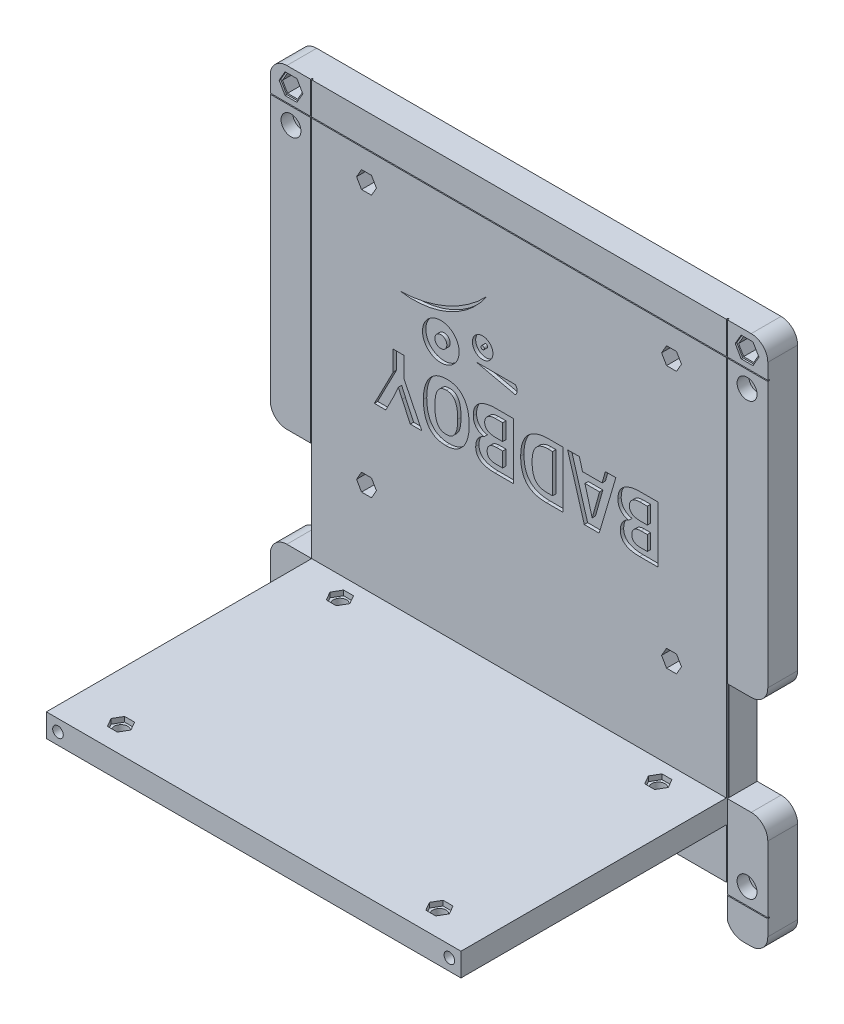
SolidWorks part; units mm, degrees
ref_plane "前基準面" through (0, 0, 0) normal (0, 0, 1) x (1, 0, 0)
ref_plane "上基準面" through (0, 0, 0) normal (0, 1, 0) x (1, 0, 0)
ref_plane "右基準面" through (0, 0, 0) normal (1, 0, 0) x (0, 0, -1)
sketch "草圖1" plane through (0, 0, 0) normal (0, 0, 1) x (1, 0, 0)
  line L0 (-82.0312, 77.5) -> (67.9688, 77.5)
  line L1 (-82.0312, 87.5) -> (67.9688, 87.5)
  line L2 (-82.0312, 87.5) -> (-82.0312, -72.5)
  line L3 (-82.0312, -72.5) -> (67.9688, -72.5)
  line L4 (67.9688, 87.5) -> (67.9688, -72.5)
  line L5 (-82.0312, 87.5) -> (67.9688, -72.5) construction
  line L6 (70, 77.5) -> (67.9688, 87.5)
  line L11 (-69.5312, 87.5) -> (-69.5312, -72.5)
  line L12 (55.4688, 87.5) -> (55.4688, -72.5)
  line L17 (-82.0312, 87.5) -> (-69.5312, 77.5)
  line L19 (-82.0312, 77.5) -> (-69.5312, 87.5)
  line L22 (-79.3612, 82.5) -> (-77.5712, 79.3996)
  line L23 (-77.5712, 79.3996) -> (-73.9912, 79.3996)
  line L24 (-73.9912, 79.3996) -> (-72.2012, 82.5)
  line L25 (-72.2012, 82.5) -> (-73.9912, 85.6004)
  line L26 (-73.9912, 85.6004) -> (-77.5712, 85.6004)
  line L27 (-77.5712, 85.6004) -> (-79.3612, 82.5)
  line L30 (55.4688, 87.5) -> (67.9688, 77.5)
  line L31 (67.9688, -62.5) -> (-82.0312, -62.5)
  line L32 (63.5088, 85.6004) -> (59.9288, 85.6004)
  line L33 (59.9288, 85.6004) -> (58.1388, 82.5)
  line L34 (58.1388, 82.5) -> (59.9288, 79.3996)
  line L35 (59.9288, 79.3996) -> (63.5088, 79.3996)
  line L36 (63.5088, 79.3996) -> (65.2988, 82.5)
  line L37 (65.2988, 82.5) -> (63.5088, 85.6004)
  line L38 (67.9688, -72.5) -> (55.4688, -62.5)
  line L39 (55.4688, -72.5) -> (67.9688, -62.5)
  line L40 (-82.0312, -72.5) -> (-69.5312, -62.5)
  line L41 (-69.5312, -72.5) -> (-82.0312, -62.5)
  line L43 (-77.5712, -64.3996) -> (-79.3612, -67.5)
  line L44 (-79.3612, -67.5) -> (-77.5712, -70.6004)
  line L45 (-77.5712, -70.6004) -> (-73.9912, -70.6004)
  line L46 (-73.9912, -70.6004) -> (-72.2012, -67.5)
  line L47 (-72.2012, -67.5) -> (-73.9912, -64.3996)
  line L48 (-73.9912, -64.3996) -> (-77.5712, -64.3996)
  line L49 (58.1388, -67.5) -> (59.9288, -70.6004)
  line L50 (59.9288, -70.6004) -> (63.5088, -70.6004)
  line L51 (63.5088, -70.6004) -> (65.2988, -67.5)
  line L52 (65.2988, -67.5) -> (63.5088, -64.3996)
  line L53 (63.5088, -64.3996) -> (59.9288, -64.3996)
  line L54 (59.9288, -64.3996) -> (58.1388, -67.5)
  circle A0 centre (-60.98, 68.98) radius 3.1
  circle A1 centre (-60.98, -10.02) radius 3.1
  circle A5 centre (-75.7812, 82.5) radius 3.1004 construction
  circle A6 centre (61.7188, 82.5) radius 3.1004 construction
  circle A7 centre (-75.7812, -67.5) radius 3.1004 construction
  circle A8 centre (61.7188, -67.5) radius 3.1004 construction
  point P0 (0, 0)
  dimension "D8" = 8.52
  dimension "D10" = 79
  dimension "D11" = 5
  dimension "D13" = 3.58
  dimension "D1" = 160
  dimension "D2" = 150
  dimension "D3" = 6.25
  dimension "D4" = 6.25
  dimension "D5" = 12.5
  dimension "D6" = 12.5
  dimension "D7" = 10
  dimension "D9" = 5
  dimension "D12" = 5
  dimension "D14" = 3.58
  dimension "D15" = 10
  dimension "D16" = 3.58
  dimension "D17" = 3.58
  dimension "D18" = 5
  dimension "D19" = 6.25
  dimension "D20" = 6.25
extrude "填料-伸長5" add sketch "草圖1" along normal blind 9 contours L2 L1 L4 L3
sketch "草圖10" plane through (0, 0, 9) normal (0, 0, 1) x (1, 0, 0)
  line L0 (-82.0312, -62.5) -> (67.9688, -62.5)
  line L1 (-82.0312, 87.5) -> (-82.0312, -72.5) construction
  line L2 (67.9688, 87.5) -> (67.9688, -72.5) construction
  line L3 (-82.0312, -72.5) -> (67.9688, -72.5) construction
  line L4 (-69.5312, 87.5) -> (-69.5312, -72.5)
  line L5 (-82.0312, 87.5) -> (67.9688, 87.5) construction
  line L6 (-82.0312, -62.5) -> (-69.5312, -72.5)
  line L8 (-72.2012, -67.5) -> (-73.9912, -64.3996)
  line L9 (-73.9912, -64.3996) -> (-77.5712, -64.3996)
  line L10 (-77.5712, -64.3996) -> (-79.3612, -67.5)
  line L11 (-79.3612, -67.5) -> (-77.5712, -70.6004)
  line L12 (-77.5712, -70.6004) -> (-73.9912, -70.6004)
  line L13 (-73.9912, -70.6004) -> (-72.2012, -67.5)
  circle A0 centre (-75.7812, -67.5) radius 3.1004 construction
  dimension "D1" = 10
  dimension "D2" = 12.5
  dimension "D3" = 3.58
sketch "草圖11" plane through (0, 0, 9) normal (0, 0, 1) x (1, 0, 0)
  line L0 (55.4688, 87.5) -> (55.4688, -72.5)
  line L1 (-82.0312, 87.5) -> (67.9688, 87.5) construction
  line L2 (-82.0312, -72.5) -> (67.9688, -72.5) construction
  line L3 (67.9688, -62.5) -> (-82.0312, -62.5)
  line L4 (67.9688, 87.5) -> (67.9688, -72.5) construction
  line L5 (-82.0312, 87.5) -> (-82.0312, -72.5) construction
  line L6 (67.9688, -62.5) -> (55.4688, -72.5)
  line L8 (65.2988, -67.5) -> (63.5088, -64.3996)
  line L9 (63.5088, -64.3996) -> (59.9288, -64.3996)
  line L10 (59.9288, -64.3996) -> (58.1388, -67.5)
  line L11 (58.1388, -67.5) -> (59.9288, -70.6004)
  line L12 (59.9288, -70.6004) -> (63.5088, -70.6004)
  line L13 (63.5088, -70.6004) -> (65.2988, -67.5)
  circle A0 centre (61.7188, -67.5) radius 3.1004 construction
  dimension "D1" = 10
  dimension "D2" = 12.5
  dimension "D3" = 3.58
sketch "草圖12" plane through (0, 0, 9) normal (0, 0, 1) x (1, 0, 0)
  line L0 (-82.0312, 87.5) -> (67.9688, 87.5) construction
  line L1 (-69.5312, 87.5) -> (-69.5312, -72.5)
  line L2 (-82.0312, -72.5) -> (67.9688, -72.5) construction
  line L3 (-69.5312, -72.5) -> (-69.8312, -72.5)
  line L4 (-69.8312, -72.5) -> (-69.8312, 87.5)
  line L5 (-69.8312, 87.5) -> (-69.5312, 87.5)
  line L6 (-82.0312, 87.5) -> (-82.0312, -72.5) construction
  dimension "D1" = 0.3
  dimension "D2" = 12.5
extrude "除料-伸長8" cut sketch "草圖12" against normal blind 0.5 contours L5 L1 L3 L4
sketch "草圖13" plane through (0, 0, 9) normal (0, 0, 1) x (1, 0, 0)
  line L0 (55.4688, 87.5) -> (55.4688, -72.5)
  line L1 (-69.5312, 87.5) -> (67.9688, 87.5) construction
  line L2 (-69.5312, -72.5) -> (67.9688, -72.5) construction
  line L3 (55.4688, -72.5) -> (55.7675, -72.5)
  line L4 (55.7675, -72.5) -> (55.7675, 87.5)
  line L5 (55.7675, 87.5) -> (55.4688, 87.5)
  line L6 (67.9688, 87.5) -> (67.9688, -72.5) construction
  dimension "D1" = 0.2988
  dimension "D2" = 12.5
extrude "除料-伸長9" cut sketch "草圖13" against normal blind 0.5 contours L5 L0 L3 L4
sketch "草圖19" plane through (0, 0, 9) normal (0, 0, 1) x (1, 0, 0)
  line L0 (-82.0312, 77.5) -> (-69.5312, 77.5)
  line L1 (-82.0312, 87.5) -> (-82.0312, -72.5) construction
  line L2 (-69.5312, 87.5) -> (-69.5312, -72.5) construction
  line L3 (-82.0312, 87.5) -> (-69.8312, 87.5) construction
  line L4 (-82.0312, 87.5) -> (-69.5312, 77.5)
  line L5 (-69.5312, 87.5) -> (-82.0312, 77.5)
  line L7 (-72.2012, 82.5) -> (-73.9912, 85.6004)
  line L8 (-73.9912, 85.6004) -> (-77.5712, 85.6004)
  line L9 (-77.5712, 85.6004) -> (-79.3612, 82.5)
  line L10 (-79.3612, 82.5) -> (-77.5712, 79.3996)
  line L11 (-77.5712, 79.3996) -> (-73.9912, 79.3996)
  line L12 (-73.9912, 79.3996) -> (-72.2012, 82.5)
  circle A0 centre (-75.7812, 82.5) radius 3.1004 construction
  dimension "D1" = 10
  dimension "D2" = 3.58
  dimension "D3" = 5
  dimension "D4" = 6.25
extrude "除料-伸長22" cut sketch "草圖19" against normal blind 0.5 contours L7 L8 L9 L10 L11 L12
sketch "草圖22" plane through (0, 0, 8.5) normal (0, 0, 1) x (1, 0, 0)
  line L0 (-77.5712, 85.6004) -> (-73.9912, 79.3996)
  line L2 (-72.7312, 82.5) -> (-74.2562, 85.1414)
  line L3 (-74.2562, 85.1414) -> (-77.3062, 85.1414)
  line L4 (-77.3062, 85.1414) -> (-78.8312, 82.5)
  line L5 (-78.8312, 82.5) -> (-77.3062, 79.8586)
  line L6 (-77.3062, 79.8586) -> (-74.2562, 79.8586)
  line L7 (-74.2562, 79.8586) -> (-72.7312, 82.5)
  line L8 (-82.0312, 87.5) -> (-69.8312, 87.5) construction
  circle A0 centre (-75.7812, 82.5) radius 2.6414 construction
  dimension "3.1" = 3.05
  dimension "D2" = 3.58
  dimension "D3" = 5
extrude "除料-伸長23" cut sketch "草圖22" against normal blind 4 contours L2 L3 L4 L5 L6 L7
sketch "草圖26" plane through (0, 0, 9) normal (0, 0, 1) x (1, 0, 0)
  line L0 (-82.0312, 77.5) -> (67.9688, 77.5)
  line L1 (-82.0312, 87.5) -> (-82.0312, -72.5) construction
  line L2 (67.9688, 87.5) -> (67.9688, -72.5) construction
  line L3 (67.9688, 77.5) -> (67.9688, 77.8)
  line L4 (67.9688, 77.8) -> (-82.0312, 77.8)
  line L5 (-82.0312, 77.8) -> (-82.0312, 77.5)
  line L6 (-82.0312, 87.5) -> (-69.8312, 87.5) construction
  line L7 (-69.8312, -72.5) -> (-69.8312, 87.5) construction
  dimension "D1" = 0.3
  dimension "D2" = 10
  dimension "D3" = 90
extrude "除料-伸長27" cut sketch "草圖26" against normal blind 0.5 contours L5 L0 L3 L4
sketch "草圖27" plane through (0, 0, 9) normal (0, 0, 1) x (1, 0, 0)
  line L0 (-82.0312, -62.5) -> (67.9688, -62.5)
  line L1 (-82.0312, 77.5) -> (-82.0312, -72.5) construction
  line L2 (67.9688, 77.5) -> (67.9688, -72.5) construction
  line L3 (67.9688, -62.5) -> (67.9688, -62.8)
  line L4 (67.9688, -62.8) -> (-82.0312, -62.8)
  line L5 (-82.0312, -62.8) -> (-82.0312, -62.5)
  line L6 (-82.0312, -72.5) -> (-69.8312, -72.5) construction
  dimension "D1" = 0.3
  dimension "D2" = 10
extrude "除料-伸長28" cut sketch "草圖27" against normal blind 0.5 contours L5 L0 L3 L4
sketch "草圖32" plane through (0, 0, 9) normal (0, 0, 1) x (1, 0, 0)
  line L0 (55.4688, 87.5) -> (67.9688, 77.5)
  line L1 (67.9688, 87.5) -> (67.9688, 77.8) construction
  line L2 (65.2988, 82.5) -> (63.5088, 85.6004)
  line L3 (63.5088, 85.6004) -> (59.9288, 85.6004)
  line L4 (59.9288, 85.6004) -> (58.1388, 82.5)
  line L5 (58.1388, 82.5) -> (59.9288, 79.3996)
  line L6 (59.9288, 79.3996) -> (63.5088, 79.3996)
  line L7 (63.5088, 79.3996) -> (65.2988, 82.5)
  line L8 (55.7675, 87.5) -> (67.9688, 87.5) construction
  circle A0 centre (61.7188, 82.5) radius 3.1004 construction
  dimension "D1" = 3.58
  dimension "D2" = 6.25
  dimension "D3" = 5
extrude "除料-伸長30" cut sketch "草圖32" against normal blind 0.5 contours L2 L3 L4 L5 L6 L7
sketch "草圖33" plane through (0, 0, 8.5) normal (0, 0, 1) x (1, 0, 0)
  line L0 (59.9288, 85.6004) -> (63.5088, 79.3996)
  line L1 (67.9688, 77.8) -> (55.7675, 77.8) construction
  line L2 (64.7688, 82.5) -> (63.2438, 85.1414)
  line L3 (63.2438, 85.1414) -> (60.1938, 85.1414)
  line L4 (60.1938, 85.1414) -> (58.6688, 82.5)
  line L5 (58.6688, 82.5) -> (60.1937, 79.8586)
  line L6 (60.1937, 79.8586) -> (63.2438, 79.8586)
  line L7 (63.2438, 79.8586) -> (64.7688, 82.5)
  line L8 (63.5088, 85.6004) -> (59.9288, 85.6004) construction
  circle A0 centre (61.7188, 82.5) radius 2.6414 construction
  point P3 (61.7188, 82.5)
  dimension "D1" = 3.05
  dimension "D2" = 4.7
extrude "除料-伸長31" cut sketch "草圖33" against normal blind 4 contours L2 L3 L4 L5 L6 L7
sketch "草圖34" plane through (0, 0, 9) normal (0, 0, 1) x (1, 0, 0)
  line L0 (-69.5312, -32.5) -> (55.4688, -32.5)
  line L1 (-69.5312, 77.5) -> (-69.5312, -62.5) construction
  line L2 (55.4688, 77.5) -> (55.4688, -62.5) construction
  line L3 (-69.5312, 77.5) -> (55.4688, 77.5) construction
  line L4 (-62.0312, 77.5) -> (-62.0312, -32.5)
  line L5 (-69.5312, 77.5) -> (55.4688, 77.5) construction
  line L6 (47.9688, 77.5) -> (47.9688, -32.5)
  circle A0 centre (-53.0112, 68.98) radius 3.3
  circle A1 centre (38.9488, 68.98) radius 3.3
  circle A2 centre (-53.0112, -10.02) radius 3.3
  circle A3 centre (38.9488, -10.02) radius 3.3
  dimension "D5" = 8.52
  dimension "D7" = 79
  dimension "D1" = 110
  dimension "D2" = 7.5
  dimension "D3" = 7.5
  dimension "D4" = 110
  dimension "D6" = 9.02
  dimension "D8" = 9.02
  dimension "D9" = 91.96
sketch "草圖38" plane through (0, 0, 9) normal (0, 0, 1) x (1, 0, 0)
  line L0 (-69.5312, -32.5) -> (55.4688, -32.5)
  line L1 (-69.5312, 77.5) -> (-69.5312, -62.5) construction
  line L2 (55.4688, 77.5) -> (55.4688, -62.5) construction
  line L3 (-69.5312, 77.5) -> (55.4688, 77.5) construction
  line L4 (-69.5312, -37.5) -> (55.4688, -37.5)
  line L5 (-69.5312, -44.5) -> (55.4688, -44.5)
  line L6 (-69.5312, -37.5) -> (-69.5312, -44.5)
  line L7 (55.4688, -37.5) -> (55.4688, -44.5)
  line M11 (55.4688, -62.5) -> (55.4688, 77.5)
  line M13 (-69.5312, 77.5) -> (-69.5312, -62.5)
  dimension "D1" = 110
  dimension "D2" = 5
  dimension "D3" = 7
extrude "填料-伸長6" add sketch "草圖38" along normal blind 80 contours L5 L4 M13 M11
sketch "草圖41" plane through (0, -44.5, 0) normal (0, -1, 0) x (1, 0, 0)
  line L0 (-59.5312, 89) -> (-59.5312, 9)
  line L1 (-69.5312, 89) -> (55.4688, 89) construction
  line L2 (-69.5312, 9) -> (55.4688, 9) construction
  line L3 (-69.5312, 85.5) -> (55.4688, 85.5)
  line L4 (-69.5312, 89) -> (-69.5312, 9) construction
  line L5 (55.4688, 89) -> (55.4688, 9) construction
  line L6 (45.4688, 89) -> (45.4688, 9)
  line L7 (-59.5312, 10.5) -> (45.4688, 10.5)
  line L8 (-69.5312, 9) -> (55.4688, 9) construction
  circle A0 centre (-55.0312, 81) radius 3
  circle A1 centre (40.9688, 81) radius 3
  circle A2 centre (-55.0312, 15) radius 3
  circle A3 centre (40.9688, 15) radius 3
  dimension "D4" = 4.5
  dimension "D1" = 10
  dimension "D2" = 3.5
  dimension "D3" = 10
  dimension "D5" = 4.5
  dimension "D6" = 4.5
  dimension "D7" = 4.5
  dimension "D8" = 1.5
  dimension "D9" = 4.5
  dimension "D10" = 4.5
  dimension "D11" = 4.5
  dimension "D12" = 4.5
extrude "填料-伸長8" add sketch "草圖41" along normal blind 3 contours A0 | A2 | A3 | A1
sketch "草圖42" plane through (0, -47.5, 0) normal (0, -1, 0) x (1, 0, 0)
  circle A0 centre (-55.0312, 81) radius 2
  circle A1 centre (40.9688, 81) radius 2
  circle A2 centre (-55.0312, 15) radius 2
  circle A3 centre (40.9688, 15) radius 2
extrude "除料-伸長37" cut sketch "草圖42" against normal blind 12 contours A0 | A1 | A3 | A2
sketch "草圖44" plane through (0, 0, 0) normal (0, 0, -1) x (-1, 0, 0)
  line L0 (-67.9688, 77.5) -> (82.0312, 77.5)
  line L1 (82.0312, 87.5) -> (82.0312, -72.5) construction
  line L2 (-55.4688, 87.5) -> (-55.4688, -72.5)
  line L3 (82.0312, 87.5) -> (-67.9688, 87.5) construction
  line L4 (82.0312, -72.5) -> (-67.9688, -72.5) construction
  line L5 (69.5312, -72.5) -> (69.5312, 87.5)
  line L6 (-67.9688, -62.5) -> (82.0312, -62.5)
  line L7 (-67.9688, 87.5) -> (-67.9688, -72.5) construction
  line L8 (-67.9688, 67.5) -> (82.0312, 67.5)
  line L9 (-67.9688, -52.5) -> (82.0312, -52.5)
  line L10 (-67.9688, 77.5) -> (-55.4688, 67.5)
  line L11 (69.5312, 77.5) -> (82.0312, 67.5)
  line L12 (-58.1388, 72.5) -> (-59.9288, 75.6004)
  line L13 (-59.9288, 75.6004) -> (-63.5088, 75.6004)
  line L14 (-63.5088, 75.6004) -> (-65.2988, 72.5)
  line L15 (-65.2988, 72.5) -> (-63.5088, 69.3996)
  line L16 (-63.5088, 69.3996) -> (-59.9288, 69.3996)
  line L17 (-59.9288, 69.3996) -> (-58.1388, 72.5)
  line L18 (82.0312, -52.5) -> (69.5312, -62.5)
  line L19 (79.3612, 72.5) -> (77.5712, 75.6004)
  line L20 (77.5712, 75.6004) -> (73.9912, 75.6004)
  line L21 (73.9912, 75.6004) -> (72.2012, 72.5)
  line L22 (72.2012, 72.5) -> (73.9912, 69.3996)
  line L23 (73.9912, 69.3996) -> (77.5712, 69.3996)
  line L24 (77.5712, 69.3996) -> (79.3612, 72.5)
  line L25 (-67.9688, -52.5) -> (-55.4688, -62.5)
  line L26 (79.3612, -57.5) -> (77.5712, -54.3996)
  line L27 (77.5712, -54.3996) -> (73.9912, -54.3996)
  line L28 (73.9912, -54.3996) -> (72.2012, -57.5)
  line L29 (72.2012, -57.5) -> (73.9912, -60.6004)
  line L30 (73.9912, -60.6004) -> (77.5712, -60.6004)
  line L31 (77.5712, -60.6004) -> (79.3612, -57.5)
  line L33 (-58.1388, -57.5) -> (-59.9288, -54.3996)
  line L34 (-59.9288, -54.3996) -> (-63.5088, -54.3996)
  line L35 (-63.5088, -54.3996) -> (-65.2988, -57.5)
  line L36 (-65.2988, -57.5) -> (-63.5088, -60.6004)
  line L37 (-63.5088, -60.6004) -> (-59.9288, -60.6004)
  line L38 (-59.9288, -60.6004) -> (-58.1388, -57.5)
  circle A0 centre (-61.7188, 72.5) radius 3.1004 construction
  circle A1 centre (75.7812, 72.5) radius 3.1004 construction
  circle A2 centre (75.7812, -57.5) radius 3.1004 construction
  circle A3 centre (-61.7188, -57.5) radius 3.1004 construction
  dimension "D1" = 10
  dimension "D2" = 12.5
  dimension "D3" = 10
  dimension "D4" = 12.5
  dimension "D5" = 10
  dimension "D6" = 10
  dimension "D7" = 3.58
  dimension "D8" = 3.58
  dimension "D9" = 3.58
  dimension "D10" = 3.58
extrude "除料-伸長39" cut sketch "草圖44" against normal blind 0.5 contours L13 L14 L15 L16 L17 L12 | L34 L35 L36 L37 L38 L33 | L27 L28 L29 L30 L31 L26 | L20 L21 L22 L23 L24 L19
sketch "草圖45" plane through (0, 0, 0.5) normal (0, 0, -1) x (-1, 0, 0)
  line L0 (-63.5088, 75.6004) -> (-59.9288, 69.3996)
  line L1 (77.5712, 75.6004) -> (73.9912, 69.3996)
  line L2 (-58.7188, 72.5) -> (-60.2188, 75.0981)
  line L3 (-60.2188, 75.0981) -> (-63.2188, 75.0981)
  line L4 (-63.2188, 75.0981) -> (-64.7188, 72.5)
  line L5 (-64.7188, 72.5) -> (-63.2188, 69.9019)
  line L6 (-63.2188, 69.9019) -> (-60.2188, 69.9019)
  line L7 (-60.2188, 69.9019) -> (-58.7188, 72.5)
  line L8 (73.9912, -54.3996) -> (77.5712, -60.6004)
  line L9 (78.7812, 72.5) -> (77.2812, 75.0981)
  line L10 (77.2812, 75.0981) -> (74.2812, 75.0981)
  line L11 (74.2812, 75.0981) -> (72.7812, 72.5)
  line L12 (72.7812, 72.5) -> (74.2812, 69.9019)
  line L13 (74.2812, 69.9019) -> (77.2812, 69.9019)
  line L14 (77.2812, 69.9019) -> (78.7812, 72.5)
  line L15 (-63.5088, -54.3996) -> (-59.9288, -60.6004)
  line L16 (78.7812, -57.5) -> (77.2812, -54.9019)
  line L17 (77.2812, -54.9019) -> (74.2812, -54.9019)
  line L18 (74.2812, -54.9019) -> (72.7812, -57.5)
  line L19 (72.7812, -57.5) -> (74.2812, -60.0981)
  line L20 (74.2812, -60.0981) -> (77.2812, -60.0981)
  line L21 (77.2812, -60.0981) -> (78.7812, -57.5)
  line L23 (-58.7188, -57.5) -> (-60.2188, -54.9019)
  line L24 (-60.2188, -54.9019) -> (-63.2188, -54.9019)
  line L25 (-63.2188, -54.9019) -> (-64.7188, -57.5)
  line L26 (-64.7188, -57.5) -> (-63.2188, -60.0981)
  line L27 (-63.2188, -60.0981) -> (-60.2188, -60.0981)
  line L28 (-60.2188, -60.0981) -> (-58.7188, -57.5)
  circle A0 centre (-61.7188, 72.5) radius 2.5981 construction
  circle A1 centre (75.7812, 72.5) radius 2.5981 construction
  circle A2 centre (75.7812, -57.5) radius 2.5981 construction
  circle A3 centre (-61.7188, -57.5) radius 2.5981 construction
  dimension "D1" = 3
  dimension "D2" = 3
  dimension "D3" = 3
  dimension "D4" = 3
extrude "除料-伸長40" cut sketch "草圖45" against normal blind 1.5 contours L3 L4 L5 L6 L7 L2 | L24 L25 L26 L27 L28 L23 | L17 L18 L19 L20 L21 L16 | L10 L11 L12 L13 L14 L9
sketch "草圖46" plane through (0, 0, 2) normal (0, 0, -1) x (-1, 0, 0)
  line L0 (-63.2188, 75.0981) -> (-60.2188, 69.9019)
  line L1 (74.2812, 75.0981) -> (77.2812, 69.9019)
  line L2 (74.2812, -54.9019) -> (77.2812, -60.0981)
  line L3 (-63.2188, -54.9019) -> (-60.2188, -60.0981)
  circle A0 centre (-61.7188, 72.5) radius 1.6
  circle A1 centre (75.7812, 72.5) radius 1.6
  circle A2 centre (75.7812, -57.5) radius 1.6
  circle A3 centre (-61.7188, -57.5) radius 1.6
extrude "除料-伸長41" cut sketch "草圖46" against normal blind 5.5 contours A0 | A1 | A2 | A3
sketch "草圖53" plane through (0, 0, 89) normal (0, 0, 1) x (1, 0, 0)
  line L0 (-62.5312, -37.5) -> (-62.5312, -44.5)
  line L1 (-69.5312, -37.5) -> (55.4688, -37.5) construction
  line L2 (-69.5312, -44.5) -> (55.4688, -44.5) construction
  line L3 (-69.5312, 77.5) -> (-69.5312, -62.5) construction
  line L4 (-69.5312, -37.5) -> (-62.5312, -44.5)
  line L5 (48.4688, -37.5) -> (48.4688, -44.5)
  line L6 (-69.5312, -44.5) -> (55.4688, -44.5) construction
  line L7 (55.4688, -44.5) -> (55.4688, -37.5) construction
  line L8 (48.4688, -37.5) -> (55.4688, -44.5)
  circle A0 centre (-66.0312, -41) radius 1.6
  circle A1 centre (51.9688, -41) radius 1.6
  dimension "D2" = 7
  dimension "D1" = 7
extrude "除料-伸長45" cut sketch "草圖53" against normal blind 7 contours A0 | A1
sketch "草圖54" plane through (0, 0, 9) normal (0, 0, 1) x (1, 0, 0)
  line L1 (-69.5312, -59.5) -> (55.4688, -59.5)
  line L2 (-69.5312, -59.5) -> (-69.5312, -72.5)
  line L3 (-69.5312, -72.5) -> (55.4688, -72.5)
  line L4 (55.4688, -59.5) -> (55.4688, -72.5)
  point P6 (0, 0)
  point P7 (0, 0)
  dimension "D1" = 13
extrude "除料-伸長46" cut sketch "草圖54" against normal blind 10
sketch "草圖56" plane through (0, 0, 0) normal (0, 0, -1) x (-1, 0, 0)
  circle A7 centre (-38.9488, 68.98) radius 3.5
  circle A8 centre (53.0112, 68.98) radius 3.5
  circle A9 centre (53.0112, -10.02) radius 3.5
  circle A10 centre (-38.9488, -10.02) radius 3.5
extrude "填料-伸長11" add sketch "草圖56" along normal blind 5
ref_plane "平面1" through (0, 0, 11) normal (0, 0, 1) x (1, 0, 0)
sketch "草圖58" plane through (0, 0, 11) normal (0, 0, 1) x (1, 0, 0)
  line L25 (41.9488, -10.02) -> (40.4488, -7.4219)
  line L26 (40.4488, -7.4219) -> (37.4488, -7.4219)
  line L27 (37.4488, -7.4219) -> (35.9488, -10.02)
  line L28 (35.9488, -10.02) -> (37.4488, -12.6181)
  line L29 (37.4488, -12.6181) -> (40.4488, -12.6181)
  line L30 (40.4488, -12.6181) -> (41.9488, -10.02)
  line L31 (-50.0112, -10.02) -> (-51.5112, -7.4219)
  line L32 (-51.5112, -7.4219) -> (-54.5112, -7.4219)
  line L33 (-54.5112, -7.4219) -> (-56.0112, -10.02)
  line L34 (-56.0112, -10.02) -> (-54.5112, -12.6181)
  line L35 (-54.5112, -12.6181) -> (-51.5112, -12.6181)
  line L36 (-51.5112, -12.6181) -> (-50.0112, -10.02)
  line L37 (-50.0112, 68.98) -> (-51.5112, 71.5781)
  line L38 (-51.5112, 71.5781) -> (-54.5112, 71.5781)
  line L39 (-54.5112, 71.5781) -> (-56.0112, 68.98)
  line L40 (-56.0112, 68.98) -> (-54.5112, 66.3819)
  line L41 (-54.5112, 66.3819) -> (-51.5112, 66.3819)
  line L42 (-51.5112, 66.3819) -> (-50.0112, 68.98)
  line L43 (41.9488, 68.98) -> (40.4488, 71.5781)
  line L44 (40.4488, 71.5781) -> (37.4488, 71.5781)
  line L45 (37.4488, 71.5781) -> (35.9488, 68.98)
  line L46 (35.9488, 68.98) -> (37.4488, 66.3819)
  line L47 (37.4488, 66.3819) -> (40.4488, 66.3819)
  line L48 (40.4488, 66.3819) -> (41.9488, 68.98)
  circle A0 centre (38.9488, -10.02) radius 2.5981 construction
  circle A1 centre (-53.0112, -10.02) radius 2.5981 construction
  circle A2 centre (-53.0112, 68.98) radius 2.5981 construction
  circle A3 centre (38.9488, 68.98) radius 2.5981 construction
  dimension "D1" = 3
  dimension "D2" = 3
  dimension "D3" = 3
  dimension "D4" = 3
extrude "除料-伸長47" cut sketch "草圖58" against normal blind 12.5
sketch "草圖59" plane through (0, 0, 11) normal (0, 0, 1) x (1, 0, 0)
  circle A4 centre (-53.0112, -10.02) radius 1.6
  circle A5 centre (38.9488, -10.02) radius 1.6
  circle A6 centre (38.9488, 68.98) radius 1.6
  circle A7 centre (-53.0112, 68.98) radius 1.6
extrude "除料-伸長48" cut sketch "草圖59" against normal blind 15
sketch "草圖62" plane through (0, 0, 9) normal (0, 0, 1) x (1, 0, 0)
  circle A0 centre (61.7188, 72.5) radius 3
  circle A1 centre (61.7188, -57.5) radius 3
  circle A2 centre (-75.7812, -57.5) radius 3
  circle A3 centre (-75.7812, 72.5) radius 3
extrude "除料-伸長50" cut sketch "草圖62" against normal blind 3.5
sketch "草圖63" plane through (0, 0, -5) normal (0, 0, -1) x (-1, 0, 0)
  circle A0 centre (-38.9488, 68.98) radius 3
  circle A1 centre (53.0112, 68.98) radius 3
  circle A2 centre (53.0112, -10.02) radius 3
  circle A3 centre (-38.9488, -10.02) radius 3
extrude "除料-伸長51" cut sketch "草圖63" against normal blind 2.2
sketch "草圖64" plane through (0, -37.5, 0) normal (0, 1, 0) x (1, 0, 0)
  line L1 (-52.029, -15) -> (-53.5301, -12.4)
  line L2 (-53.5301, -12.4) -> (-56.5324, -12.4)
  line L3 (-56.5324, -12.4) -> (-58.0335, -15)
  line L4 (-58.0335, -15) -> (-56.5324, -17.6)
  line L5 (-56.5324, -17.6) -> (-53.5301, -17.6)
  line L6 (-53.5301, -17.6) -> (-52.029, -15)
  line L7 (43.971, -15) -> (42.4699, -12.4)
  line L8 (42.4699, -12.4) -> (39.4676, -12.4)
  line L9 (39.4676, -12.4) -> (37.9665, -15)
  line L10 (37.9665, -15) -> (39.4676, -17.6)
  line L11 (39.4676, -17.6) -> (42.4699, -17.6)
  line L12 (42.4699, -17.6) -> (43.971, -15)
  line L13 (43.971, -81) -> (42.4699, -78.4)
  line L14 (42.4699, -78.4) -> (39.4676, -78.4)
  line L15 (39.4676, -78.4) -> (37.9665, -81)
  line L16 (37.9665, -81) -> (39.4676, -83.6)
  line L17 (39.4676, -83.6) -> (42.4699, -83.6)
  line L18 (42.4699, -83.6) -> (43.971, -81)
  line L19 (-52.029, -81) -> (-53.5301, -78.4)
  line L20 (-53.5301, -78.4) -> (-56.5324, -78.4)
  line L21 (-56.5324, -78.4) -> (-58.0335, -81)
  line L22 (-58.0335, -81) -> (-56.5324, -83.6)
  line L23 (-56.5324, -83.6) -> (-53.5301, -83.6)
  line L24 (-53.5301, -83.6) -> (-52.029, -81)
  circle A0 centre (-55.0312, -15) radius 2.6 construction
  circle A1 centre (40.9688, -15) radius 2.6 construction
  circle A2 centre (40.9688, -81) radius 2.6 construction
  circle A3 centre (-55.0312, -81) radius 2.6 construction
  dimension "D1" = 2.6
  dimension "D2" = 2.6
  dimension "D3" = 2.6
  dimension "D4" = 2.6
extrude "除料-伸長52" cut sketch "草圖64" against normal blind 1.5
sketch "草圖65" plane through (0, 0, 4.5) normal (0, 0, 1) x (1, 0, 0)
  line L0 (-77.3062, 85.1414) -> (-74.2562, 79.8586) construction
  line L1 (60.1938, 85.1414) -> (63.2438, 79.8586) construction
  circle A0 centre (61.7188, 82.5) radius 1.6
  circle A1 centre (-75.7812, 82.5) radius 1.6
extrude "除料-伸長53" cut sketch "草圖65" against normal blind 4.5
sketch "草圖66" plane through (0, 0, 0) normal (0, 0, -1) x (-1, 0, 0)
  circle A0 centre (-61.7188, 82.5) radius 2.5
  circle A1 centre (75.7812, 82.5) radius 2.5
extrude "除料-伸長54" cut sketch "草圖66" against normal blind 2.2
fillet "圓角1" radius 5 6 edges at (-69.5312, -72.5, 4.25) (-82.0312, -72.5, 4.5) (55.4688, -72.5, 4.25) (67.9688, -72.5, 4.5) (67.9688, 87.5, 4.5) (-82.0312, 87.5, 4.5)
sketch "草圖67" plane through (0, 0, 11) normal (0, 0, 1) x (1, 0, 0)
  line L4 (-69.5312, -37.5) -> (-69.8312, -37.5) construction
  line L5 (-69.8312, -62.5) -> (-69.8312, 77.5) construction
  line L6 (-69.8312, 77.5) -> (-69.8312, -7.5) construction
  line L8 (-69.8312, -37.5) -> (-82.0312, -37.5)
  line L9 (-69.8312, -37.5) -> (-69.8312, -7.5)
  line L10 (-69.8312, -7.5) -> (-82.0312, -7.5)
  line L11 (-82.0312, -37.5) -> (-82.0312, -7.5)
  line L12 (55.4688, -37.5) -> (55.7675, -37.5) construction
  line L13 (55.7675, -62.5) -> (55.7675, 77.5) construction
  line L14 (67.9688, 77.5) -> (67.9688, -7.5) construction
  line L16 (67.9688, -7.5) -> (55.7675, -7.5)
  line L17 (67.9688, -7.5) -> (67.9688, -37.5)
  line L18 (67.9688, -37.5) -> (55.7675, -37.5)
  line L19 (55.7675, -7.5) -> (55.7675, -37.5)
  dimension "D1" = 30
  dimension "D2" = 30
extrude "除料-伸長55" cut sketch "草圖67" against normal blind 12
fillet "圓角4" radius 5 4 edges at (-82.0312, -37.5, 4.5) (67.9688, -37.5, 4.5) (67.9688, -7.5, 4.5) (-82.0312, -7.5, 4.5)
sketch "草圖68" plane through (0, 0, 9) normal (0, 0, 1) x (1, 0, 0)
  line L0 (-53.0112, 68.98) -> (-53.0112, -10.02) construction
  line L1 (-53.0112, 29.48) -> (38.9488, 29.48) construction
  line L4 (38.9488, -10.02) -> (38.9488, 68.98) construction
  line L5 (-19.9352, 38.6302) -> (-8.1426, 35.974)
  line L7 (-8.1426, 38.6302) -> (-19.9352, 38.6302)
  circle A0 centre (-18.0049, 43.3278) radius 3.0956
  circle A1 centre (-30.6045, 38.6302) radius 5.5233
  arc A2 (-16.8283, 57.2248) -> (-42.9044, 45.6821) centre (-38.9358, 71.9422) cw
  arc A3 (-16.8283, 57.2248) -> (-42.9044, 45.6821) centre (-43.8363, 83.0129) cw
  arc A4 (-8.1426, 35.974) -> (-8.1426, 38.6302) centre (-9.4707, 37.3021) ccw
  circle A5 centre (-18.0049, 43.3278) radius 0.5124
  circle A6 centre (-30.6045, 38.6302) radius 1.8156
  text T0 "<b>BADBOY</b>" font "Consolas" height 17
  point P9 (-53.0112, 29.48)
  point P15 (38.9488, 29.48)
extrude "除料-伸長56" cut sketch "草圖68" against normal blind 1
